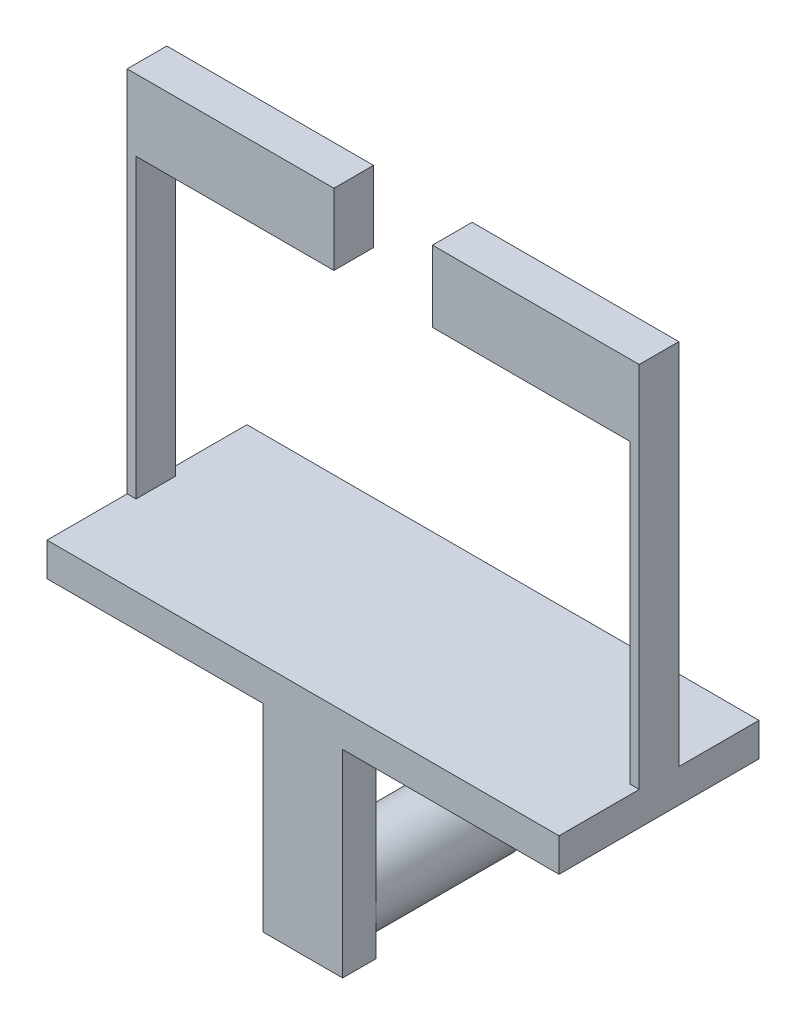
SolidWorks part; units mm, degrees
material "Ti-6Al-4V"
ref_plane "Front Plane" through (0, 0, 0) normal (0, 0, 1) x (1, 0, 0)
ref_plane "Top Plane" through (0, 0, 0) normal (0, 1, 0) x (1, 0, 0)
ref_plane "Right Plane" through (0, 0, 0) normal (1, 0, 0) x (0, 0, -1)
sketch "Sketch6" plane through (0, 0, 0) normal (0, 1, 0) x (1, 0, 0)
  line L1 (-17.2688, 11.9196) -> (-7.0707, 11.9196)
  line L2 (-17.2688, 11.9196) -> (-17.2688, 7.632)
  line L3 (-17.2688, 7.632) -> (-7.0707, 7.632)
  line L4 (-7.0707, 11.9196) -> (-7.0707, 7.632)
  dimension "D1" = 10.1981
  dimension "D2" = 4.2875
extrude "Boss-Extrude3" add sketch "Sketch6" along normal blind 25.4
sketch "Sketch8" plane through (0, 0, -11.9196) normal (0, 0, 1) x (1, 0, 0)
  line L1 (-7.0707, 0) -> (-17.2688, 0) construction
  line L6 (-17.2688, 10.1971) -> (-7.0707, 0) construction
  line L7 (-7.0707, 25.4) -> (-7.0707, 0) construction
  line L8 (-7.0707, 10.1971) -> (-17.2688, 10.1971) construction
  line L9 (-17.2688, 25.4) -> (-17.2688, 0) construction
  line L10 (-7.0707, 0) -> (-7.0707, 10.1971) construction
  line L11 (-7.0707, 10.1971) -> (-17.2688, 0) construction
  circle A0 centre (-12.1698, 5.0985) radius 5.0991
  dimension "D1" = 10.1981
extrude "Boss-Extrude5" add sketch "Sketch8" against normal blind 19.05
sketch "Sketch11" plane through (0, 25.4, 0) normal (0, 1, 0) x (1, 0, 0)
  line L0 (-17.2688, 7.632) -> (-7.0707, 7.632) construction
  line L3 (-44.998, 7.632) -> (20.6965, 7.632)
  line L4 (-44.998, 7.632) -> (-44.998, 33.286)
  line L5 (-44.998, 33.286) -> (20.6965, 33.286)
  line L6 (20.6965, 7.632) -> (20.6965, 33.286)
  dimension "D1" = 25.654
  dimension "D2" = 65.6946
extrude "Boss-Extrude10" add sketch "Sketch11" along normal blind 4.2875
sketch "Sketch16" plane through (0, 29.6875, 0) normal (0, 1, 0) x (1, 0, 0)
  line L3 (20.6965, 33.286) -> (20.6965, 7.632) construction
  line L4 (-44.998, 17.919) -> (-43.855, 17.919)
  line L7 (-44.998, 17.919) -> (-44.998, 22.999)
  line L8 (-44.998, 22.999) -> (-43.855, 22.999)
  line L9 (-43.855, 17.919) -> (-43.855, 22.999)
  line L10 (-44.998, 7.632) -> (20.6965, 7.632) construction
  line L11 (20.6965, 7.632) -> (20.6965, 33.286) construction
  line L13 (20.6965, 22.999) -> (19.5415, 22.999)
  line L14 (20.6965, 22.999) -> (20.6965, 17.919)
  line L15 (20.6965, 17.919) -> (19.5415, 17.919)
  line L16 (19.5415, 22.999) -> (19.5415, 17.919)
  dimension "D1" = 1.143
  dimension "D2" = 1.1551
  dimension "D3" = 5.08
  dimension "D4" = 5.08
extrude "Boss-Extrude11" add sketch "Sketch16" along normal blind 38.0746
sketch "Sketch17" plane through (0, 67.7621, 0) normal (0, 1, 0) x (1, 0, 0)
  line L0 (-44.998, 22.999) -> (-18.4753, 22.999) construction
  line L1 (-44.998, 17.919) -> (-41.8446, 17.919) construction
  line L2 (20.6965, 22.999) -> (-5.8261, 22.999) construction
  line L3 (-44.998, 22.999) -> (-18.4753, 22.999)
  line L4 (-44.998, 22.999) -> (-44.998, 17.919)
  line L5 (-44.998, 17.919) -> (-18.4753, 17.919)
  line L6 (-18.4753, 22.999) -> (-18.4753, 17.919)
  line L7 (20.6965, 17.919) -> (3.53, 17.919) construction
  line L9 (20.6965, 17.919) -> (-5.8261, 17.919)
  line L10 (20.6965, 17.919) -> (20.6965, 22.999)
  line L11 (20.6965, 22.999) -> (-5.8261, 22.999)
  line L12 (-5.8261, 17.919) -> (-5.8261, 22.999)
  dimension "D1" = 26.5227
  dimension "D2" = 26.5227
extrude "Boss-Extrude12" add sketch "Sketch17" along normal blind 9.144
equation "\"baseH\"= 2.5864"
equation "\"baseD\"= 1.01"
equation "\"baseT\" = 0.1688"
equation "\"cylwallH\"= 1"
equation "\"cylwallD\"= 0.4015"
equation "\"cylwallT\"= 0.1688"
equation "\"cylH\"= 1'C"
equation "\"cylD\"= 0.40146"
equation "\"cylT\"= 0.75"
equation "\"sidewallH\"= 0.045"
equation "\"sidewallD\"= 0.2"
equation "\"sidewallT\"= 1.499"
equation "\"horizwallH\"= 0.9992"
equation "\"horizwallD\"= 0.2"
equation "\"horizwallT\"= 0.356"
equation "\"E\"= 16534303"
equation "\"SF\"= 4"
equation "\"W\"= 4 * \"lbs\""
equation "\"Ys\"= 119946"
equation "\"dMAX\"= 0.005"
equation "\"lbs\"= 508"
equation "\"z\"= \"SF\" * \"W\" * ( \"cylT\" / 2 * \"Ys\" )"
equation "\"r\"= ( 4 * ( \"z\" / pi ) ) ^ ( 1 / 3 )"
